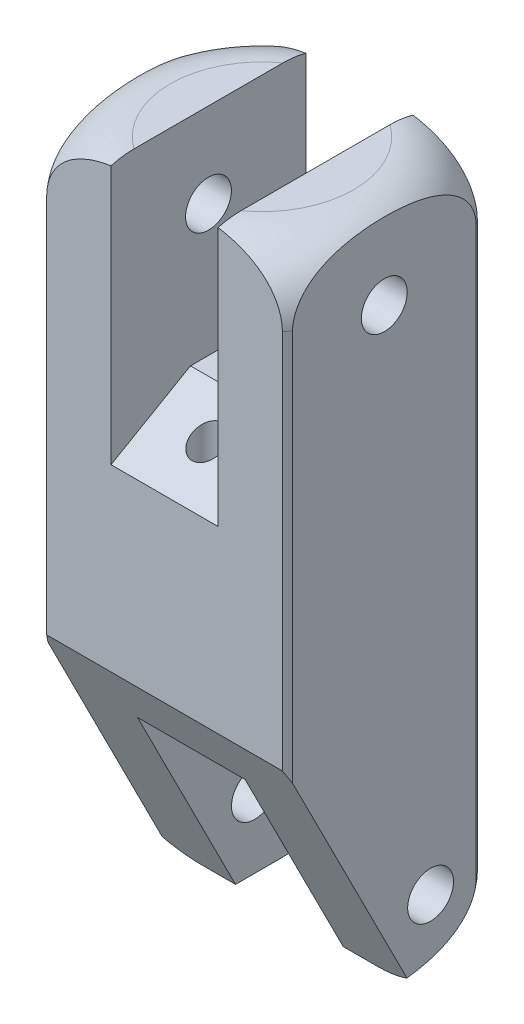
SolidWorks part; units mm, degrees
ref_plane "Front Plane" through (0, 0, 0) normal (0, 0, 1) x (1, 0, 0)
ref_plane "Top Plane" through (0, 0, 0) normal (0, 1, 0) x (1, 0, 0)
ref_plane "Right Plane" through (0, 0, 0) normal (1, 0, 0) x (0, 0, -1)
sketch "Sketch1" plane through (0, 0, 0) normal (0, 1, 0) x (1, 0, 0)
  circle A0 centre (0, 0) radius 10
extrude "Extrude1" add sketch "Sketch1" along normal blind 45
fillet "Fillet1" radius 4 2 edges at (0, 45, 10) (0, 0, 10)
sketch "Sketch2" plane through (0, 0, 0) normal (0, 0, 1) x (1, 0, 0)
  line L0 (0, 40) -> (0, 29.5527) construction
  line L3 (-3.522, -12.6711) -> (3.522, -12.6711)
  line L4 (-3.522, -12.6711) -> (-3.522, 12.6711)
  line L5 (-3.522, 12.6711) -> (3.522, 12.6711)
  line L6 (3.522, -12.6711) -> (3.522, 12.6711)
  line L7 (-3.522, -12.6711) -> (3.522, 12.6711) construction
  line L8 (-3.522, 12.6711) -> (3.522, -12.6711) construction
  line L16 (10, 22.5) -> (24.8802, 22.5) construction
  line L22 (-3.5, 54.8118) -> (3.5, 54.8118)
  line L23 (3.5, 54.8118) -> (3.5, 30.8647)
  line L24 (-3.5, 30.8647) -> (3.5, 30.8647)
  line L25 (-3.5, 54.8118) -> (-3.5, 30.8647)
  point P1 (0, 0)
  dimension "D1" = 3.5
  dimension "D2" = 3.5
extrude "Extrude2" cut sketch "Sketch2" against normal mid plane 40
sketch "Sketch5" plane through (0, 0, 0) normal (0, 1, 0) x (1, 0, 0)
  line L0 (0, -10) -> (0, -4.7764) construction
  line L1 (13.2584, 10.9303) -> (8, 10.9303)
  line L2 (-13.2584, -10.0291) -> (-8, -10.0291)
  line L3 (-13.2584, -10.0291) -> (-13.2584, 10.9303)
  line L4 (-13.2584, 10.9303) -> (-8, 10.9303)
  line L5 (-8, -10.0291) -> (-8, 10.9303)
  line L6 (8, -10.0291) -> (8, 10.9303)
  line L7 (13.2584, -10.0291) -> (8, -10.0291)
  line L8 (13.2584, -10.0291) -> (13.2584, 10.9303)
  dimension "D1" = 8
extrude "Extrude4" cut sketch "Sketch5" along normal through all
sketch "Sketch11" plane through (0, 45, 0) normal (0, 1, 0) x (1, 0, 0)
  line L0 (0, 0) -> (14.9471, 0) construction
  line L1 (10.8299, -12.004) -> (10.8299, -6.3732)
  line L2 (-11.1389, 12.004) -> (10.8299, 12.004)
  line L3 (-11.1389, 12.004) -> (-11.1389, 6.3732)
  line L4 (-11.1389, 6.3732) -> (10.8299, 6.3732)
  line L5 (10.8299, 12.004) -> (10.8299, 6.3732)
  line L6 (-11.1389, -6.3732) -> (10.8299, -6.3732)
  line L7 (-11.1389, -12.004) -> (-11.1389, -6.3732)
  line L8 (-11.1389, -12.004) -> (10.8299, -12.004)
extrude "Extrude10" cut sketch "Sketch11" against normal through all
sketch "Sketch12" plane through (-8, 0, 0) normal (-1, 0, 0) x (0, 0, 1)
  line L0 (0, 45) -> (0, 47.0797) construction
  circle A0 centre (0, 39.4623) radius 1.5
extrude "Extrude11" cut sketch "Sketch12" against normal through all
sketch "Sketch13" plane through (-8, 0, 0) normal (-1, 0, 0) x (0, 0, 1)
  line L0 (6.8184, 17.0031) -> (-1.7914, 0)
  line L2 (-4.8575, 0) -> (4.8575, 0) construction
  line L3 (-1.7914, 0) -> (6.8184, 0)
  line L4 (6.8184, 0) -> (6.8184, 17.0031)
  circle A0 centre (-3.0266, 4.561) radius 1.5
extrude "Extrude12" cut sketch "Sketch13" against normal through all
chamfer "Фаска1" distance 3 angle 60 1 edges at (0, 30.8647, 6.3732)
sketch "Эскиз1" plane through (0, 12.6711, 0) normal (0, -1, 0) x (1, 0, 0)
  circle A0 centre (-0.022, 3.5477) radius 1
extrude "Вырез-Вытянуть1" cut sketch "Эскиз1" against normal through all
